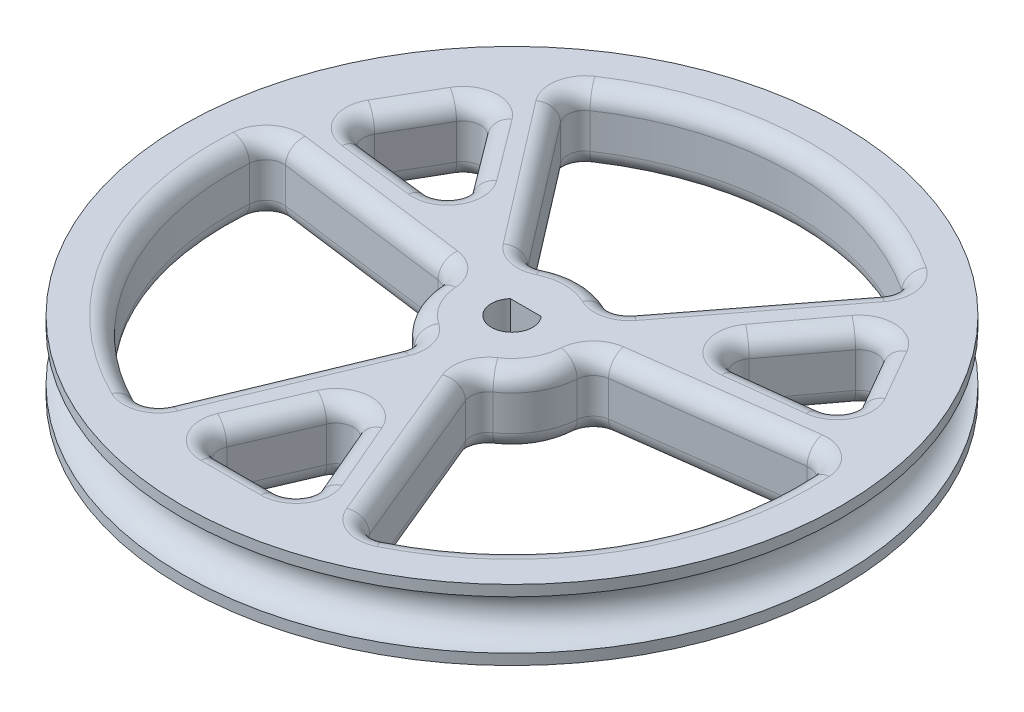
SolidWorks part; units mm, degrees
ref_plane "Front Plane" through (0, 0, 0) normal (0, 0, 1) x (1, 0, 0)
ref_plane "Top Plane" through (0, 0, 0) normal (0, 1, 0) x (1, 0, 0)
ref_plane "Right Plane" through (0, 0, 0) normal (1, 0, 0) x (0, 0, -1)
sketch "Sketch1" plane through (0, 0, 0) normal (0, 1, 0) x (1, 0, 0)
  line L0 (0, 25.5524) -> (0, 22.0218) construction
  circle A0 centre (0, 0) radius 25.5524 construction
  circle A1 centre (0, 0) radius 22.0218 construction
  circle A2 centre (0, 0) radius 23.8156
  circle A3 centre (0, 23.8156) radius 1.7938 construction
  circle A4 centre (0, 0) radius 6.35 construction
  point P34 (0, 0)
  dimension "D1" = 51.1048
  dimension "D2" = 44.0436
extrude "Boss-Extrude1" add sketch "Sketch1" along normal blind 5.08 contours A2
sketch "Sketch2" plane through (0, 5.08, 0) normal (0, 1, 0) x (1, 0, 0)
  line L0 (0, 1.4922) -> (0, -1.4922) construction
  line L1 (-1.1146, 0.9922) -> (1.1146, 0.9922) construction
  line L2 (-1.1146, 0.9922) -> (1.1146, 0.9922)
  arc A0 (-1.1146, 0.9922) -> (1.1146, 0.9922) centre (0, 0) ccw construction
  arc A1 (-1.1146, 0.9922) -> (1.1146, 0.9922) centre (0, 0) ccw
  dimension "D1" = 2.9845
  dimension "D2" = 0.5
extrude "Cut-Extrude1" cut sketch "Sketch2" against normal blind 5.08
sketch "Sketch5" plane through (0, 0, 0) normal (0, 0, 1) x (1, 0, 0)
  line L0 (0, 0) -> (-1.1146, 0)
  line L1 (0, 0) -> (-23.8156, 0) construction
  line L3 (0, 0) -> (-0.2993, -0.2058)
  line L4 (-23.8156, 5.08) -> (-23.8156, 0) construction
  line L7 (-23.8156, 0) -> (-23.8156, 5.08) construction
  line L8 (0, 4.3287) -> (0, 0) construction
  line L9 (-23.8156, 4.3053) -> (-23.8156, 0.7747)
  arc A0 (-23.8156, 0.7747) -> (-23.8156, 4.3053) centre (-23.8156, 2.54) ccw
revolve "Cut-Revolve2" cut sketch "Sketch5" angle 360 about L8
sketch "Sketch8" plane through (0, 5.08, 0) normal (0, 1, 0) x (1, 0, 0)
  line L0 (0, 0) -> (0, 0.9922)
  line L1 (1.1146, 0.9922) -> (-1.1146, 0.9922) construction
  line L2 (0, 0) -> (0, 20.32) construction
  line L3 (0, 0) -> (0, 0.9922)
  line L4 (0, 0) -> (12.37, 16.1209) construction
  line L5 (0, 0) -> (-12.37, 16.1209) construction
  line L6 (3.0925, 4.0302) -> (12.37, 16.1209)
  line L7 (0, 0.9922) -> (0, 0) construction
  line L8 (-12.37, 16.1209) -> (-3.0925, 4.0302)
  circle A0 centre (0, 0) radius 20.32 construction
  circle A1 centre (0, 0) radius 5.08 construction
  arc A2 (-12.37, 16.1209) -> (12.37, 16.1209) centre (0, 0) cw
  arc A3 (-3.0925, 4.0302) -> (3.0925, 4.0302) centre (0, 0) cw
  circle A4 centre (0, 0) radius 23.8156 construction
  dimension "D2" = 37.5
  dimension "D3" = 10.16
  dimension "D4" = 40.64
  dimension "D1" = 75
extrude "Cut-Extrude3" cut sketch "Sketch8" along direction (0, 1, 0) on the side against the normal through all contours L8 A3 L6 A2
fillet "Fillet22" radius 1.27 12 edges at (7.7313, 0, -10.0756) (7.7313, 5.08, -10.0756) (-7.7313, 0, -10.0756) (-7.7313, 5.08, -10.0756) (-3.0925, 2.54, -4.0302) (0, 0, -5.08) (3.0925, 2.54, -4.0302) (0, 5.08, -5.08) (12.37, 2.54, -16.1209) (0, 0, -20.32) (-12.37, 2.54, -16.1209) (0, 5.08, -20.32)
pattern_circular "CirPattern1" count 3 over 360 about axis through (0, 5.08, 0) along (0, 1, 0) of "Cut-Extrude3", "Fillet22"
sketch "Sketch9" plane through (0, 5.08, 0) normal (0, 1, 0) x (1, 0, 0)
  line L0 (-4.0959, -19.05) -> (4.0959, -19.05)
  line L1 (4.0959, -19.05) -> (0, -9.515)
  line L2 (0, -9.515) -> (-4.0959, -19.05)
  line L3 (0, 0) -> (0, -23.8156) construction
  circle A0 centre (0, 0) radius 23.8156 construction
  dimension "D1" = 19.05
extrude "Cut-Extrude4" cut sketch "Sketch9" along a picked direction on the side against the normal blind 5.08
fillet "Fillet23" radius 1.27 9 edges at (-4.0959, 2.54, 19.05) (0, 2.54, 9.515) (4.0959, 2.54, 19.05) (-2.0479, 5.08, 14.2825) (0, 5.08, 19.05) (2.0479, 5.08, 14.2825) (-2.0479, 0, 14.2825) (2.0479, 0, 14.2825) (0, 0, 19.05)
pattern_circular "CirPattern2" count 3 over 360 about axis through (0, 0, 0) along (0, 1, 0) of "Cut-Extrude4", "Fillet23"
